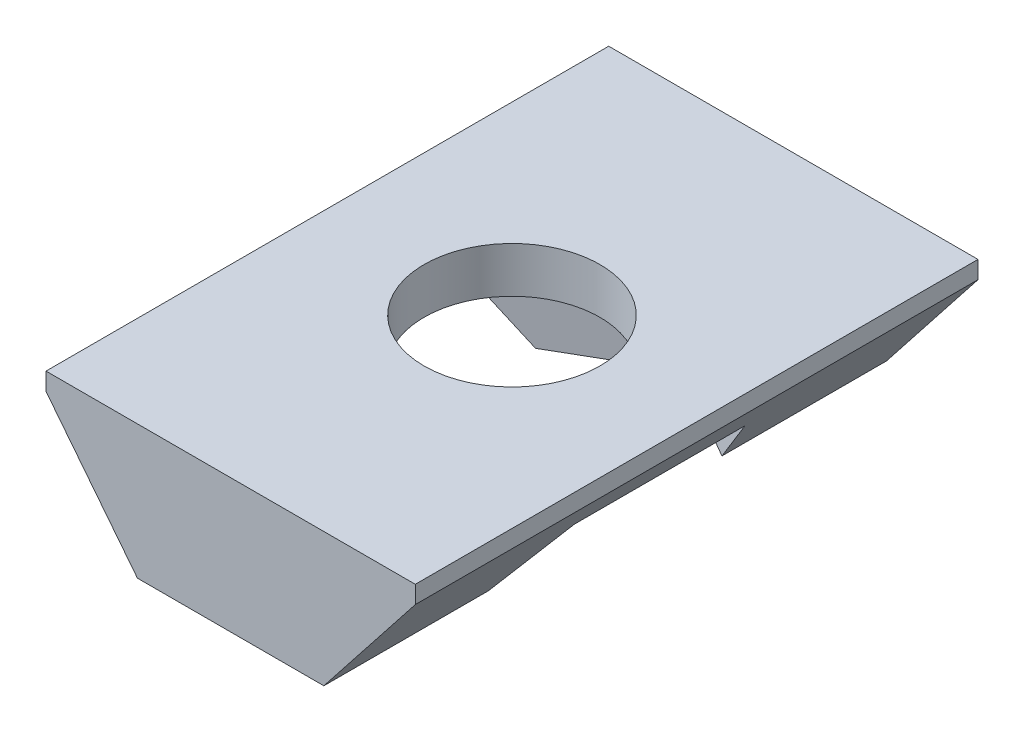
SolidWorks part; units mm, degrees
ref_plane "Plano frontal" through (0, 0, 0) normal (0, 0, 1) x (1, 0, 0)
ref_plane "Plano superior" through (0, 0, 0) normal (0, 1, 0) x (1, 0, 0)
ref_plane "Plano direito" through (0, 0, 0) normal (1, 0, 0) x (0, 0, -1)
sketch "Esboço1" plane through (0, 0, 0) normal (0, 0, 1) x (1, 0, 0)
  line L0 (-2.65, 0) -> (2.65, 0)
  line L1 (-2.65, 0) -> (-5.25, 3.3)
  line L2 (-5.25, 3.8) -> (5.25, 3.8)
  line L3 (5.25, 3.3) -> (2.65, 0)
  line L4 (0, 0) -> (0, 3.8) construction
  line L5 (5.25, 3.3) -> (5.25, 3.8)
  line L6 (-5.25, 3.3) -> (-5.25, 3.8)
  point P3 (0, 0)
  dimension "D1" = 5.3
  dimension "D2" = 10.5
  dimension "D3" = 3.8
  dimension "D4" = 0.5
extrude "Ressalto-extrusão1" add sketch "Esboço1" along normal blind 16
sketch "Esboço2" plane through (0, 3.8, 0) normal (0, 1, 0) x (1, 0, 0)
  line L0 (0, 0) -> (0, -16) construction
  line L1 (5.25, 0) -> (-5.25, 0) construction
  line L2 (5.25, -16) -> (-5.25, -16) construction
  circle A0 centre (0, -8) radius 2.5
  dimension "D1" = 5
extrude "Corte-extrusão1" cut sketch "Esboço2" against normal through all both and the other way through all
sketch "Esboço3" plane through (0, 0, 0) normal (0, -1, 0) x (1, 0, 0)
  line L1 (0, 12.8497) -> (-4.2, 10.4249)
  line L2 (-4.2, 10.4249) -> (-4.2, 5.5751)
  line L3 (-4.2, 5.5751) -> (0, 3.1503)
  line L4 (0, 3.1503) -> (4.2, 5.5751)
  line L5 (4.2, 5.5751) -> (4.2, 10.4249)
  line L6 (4.2, 10.4249) -> (0, 12.8497)
  circle A0 centre (0, 8) radius 4.2 construction
  dimension "D1" = 8.4
extrude "Corte-extrusão2" cut sketch "Esboço3" against normal blind 2.5
